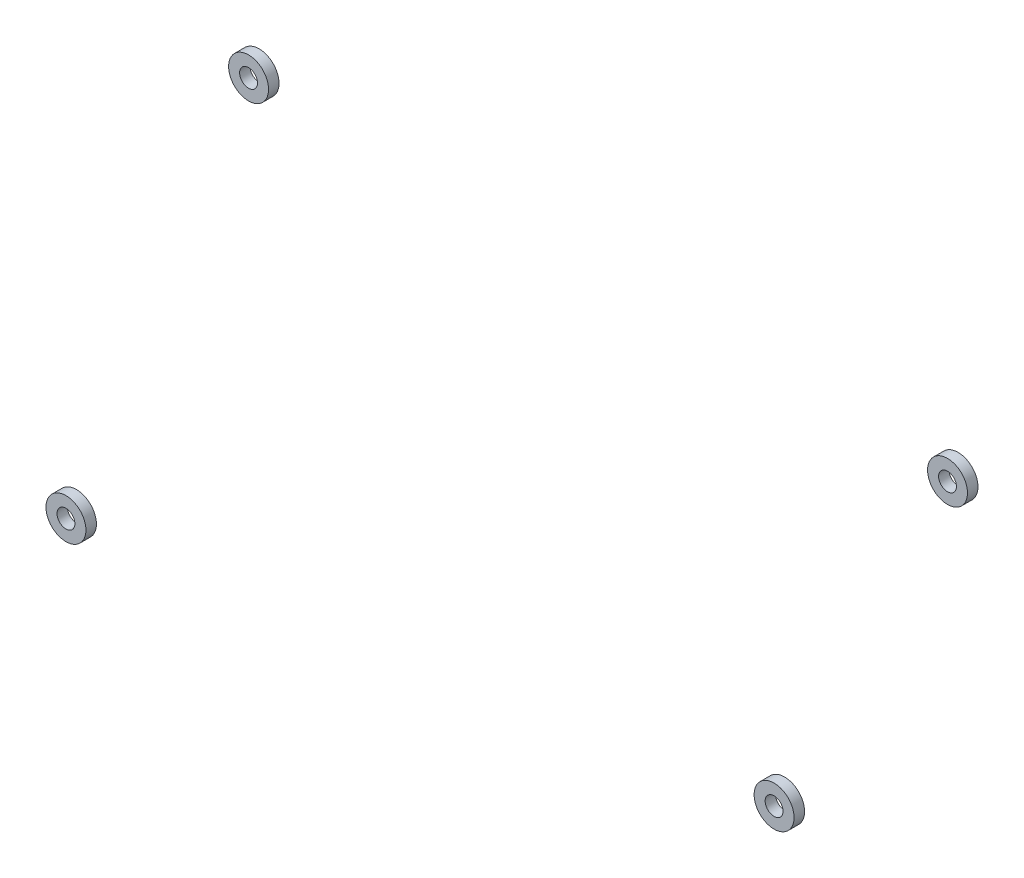
SolidWorks part; units mm, degrees
material "Custom Plastic"
ref_plane "Front Plane" through (0, 0, 0) normal (0, 0, 1) x (1, 0, 0)
ref_plane "Top Plane" through (0, 0, 0) normal (0, 1, 0) x (1, 0, 0)
ref_plane "Right Plane" through (0, 0, 0) normal (1, 0, 0) x (0, 0, -1)
sketch "Sketch1" plane through (0, 0, 0) normal (0, 0, 1) x (1, 0, 0)
  circle A0 centre (23.5, 38) radius 3.8
  circle A1 centre (156.5, 38) radius 3.8
  circle A2 centre (123.5, -32) radius 3.8
  circle A3 centre (-11.25, -52) radius 3.8
  circle A4 centre (23.5, 38) radius 1.7
  circle A5 centre (156.5, 38) radius 1.7
  circle A6 centre (-11.25, -52) radius 1.7
  circle A7 centre (123.5, -32) radius 1.7
  dimension "D1" = 7.6
  dimension "D2" = 7.6
  dimension "D3" = 7.6
  dimension "D4" = 7.6
  dimension "D5" = 3.4
  dimension "D6" = 3.4
  dimension "D7" = 3.4
  dimension "D8" = 3.4
extrude "Boss-Extrude1" add sketch "Sketch1" along normal blind 2
